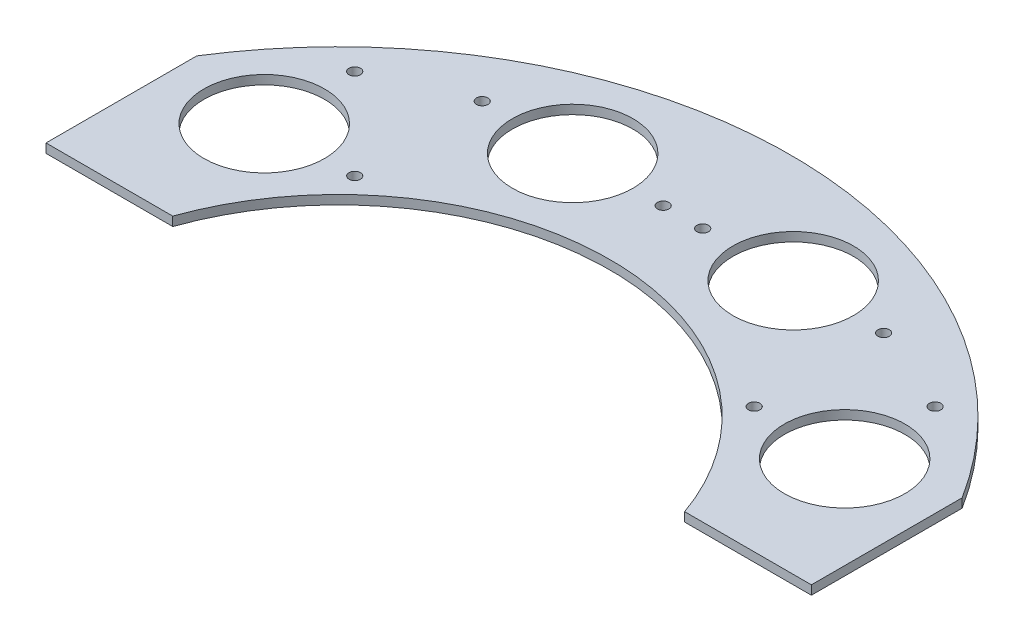
SolidWorks part; units mm, degrees
ref_plane "Front Plane" through (0, 0, 0) normal (0, 0, 1) x (1, 0, 0)
ref_plane "Top Plane" through (0, 0, 0) normal (0, 1, 0) x (1, 0, 0)
ref_plane "Right Plane" through (0, 0, 0) normal (1, 0, 0) x (0, 0, -1)
sketch "Sketch2" [suppressed] plane through (0, 0, 0) normal (0, 1, 0) x (1, 0, 0)
  line L0 (-25, 150) -> (25, 150)
  line L1 (-25, 0) -> (-25, 150) construction
  line L2 (0, 0) -> (-37.08, 101.61) construction
  line L3 (0, 0) -> (-82.9172, 69.4568) construction
  arc A0 (-25, 150) -> (0, -147.902) centre (-25, 0) ccw
  arc A1 (0, -147.902) -> (25, 150) centre (25, 0) ccw
  circle A2 centre (-37.08, 101.61) radius 20
  circle A3 centre (-82.9172, 69.4568) radius 20
  circle A4 centre (-106.5368, 18.6928) radius 20
  dimension "D1" = 300
  dimension "D2" = 300
  dimension "D5" = 40
  dimension "D3" = 50
  dimension "D4" = 25
  dimension "D6" = 12.08
  dimension "D7" = 48.39
  dimension "D9" = 30
sketch "Sketch3" plane through (0, 0, 0) normal (0, 1, 0) x (1, 0, 0)
  line L0 (-126.8858, -16.7898) -> (-84.8717, -16.7898)
  line L6 (-175, -125) -> (-139.6509, -99.7506) construction
  line L7 (-36.5556, 67.5067) -> (-27.2905, 38.9915) construction
  line L8 (-96.2239, 24.9107) -> (-71.9654, 7.2859) construction
  line L9 (-90.0178, -46.7898) -> (0, -46.7898) construction
  line L10 (0, -55) -> (0, 55) construction
  line L11 (-175, -16.7898) -> (-146.9694, -16.7898)
  line L12 (-126.8858, -16.7898) -> (-126.8858, 33.2102)
  line L13 (126.8858, -16.7898) -> (126.8858, 33.2102)
  line L14 (0, 0) -> (0, 43.228) construction
  line L17 (-19.0404, 13.6003) -> (-17.289, 8.2102) construction
  line L20 (84.8717, -16.7898) -> (126.8858, -16.7898)
  line L21 (-11.8672, -8.4766) -> (-9.166, -16.7898) construction
  circle A0 centre (-36.5556, 67.5067) radius 20
  circle A1 centre (-96.2239, 24.9107) radius 20
  circle A3 centre (36.5556, 67.5067) radius 20
  circle A4 centre (96.2239, 24.9107) radius 20
  arc A8 (84.8717, -16.7898) -> (-84.8717, -16.7898) centre (0, -46.7898) ccw
  arc A9 (126.8858, 33.2102) -> (-126.8858, 33.2102) centre (0, -46.7898) ccw
  point P0 (0, 0)
  point P2 (0, 0)
  point P10 (0, -46.7898)
  point P13 (0, 0)
  point P15 (0, 0)
  point P31 (0, 0)
  point P33 (0, 0)
  point P35 (0, 0)
  point P39 (0, 0)
  dimension "D3" = 40
  dimension "D7" = 40
  dimension "D4" = 90.0178
  dimension "D5" = 150
  dimension "D6" = 120
  dimension "D9" = 36
  dimension "D10" = 36
  dimension "D12" = 120
  dimension "D15" = 30
  dimension "D16" = 50
  dimension "D2" = 18
extrude "Boss-Extrude3" add sketch "Sketch3" along normal blind 3
hole_wizard "#10-24 Tapped Hole1" positions "Sketch4" profile "Sketch5" tap size "#10-24" standard "ANSI Inch" end condition through all
sketch "Sketch4" plane through (0, 3, 0) normal (0, 1, 0) x (1, 0, 0)
  point P0 (-66.2239, 24.9107)
  point P2 (-96.2239, 54.9107)
  point P4 (-66.5556, 67.5067)
  point P6 (-6.5556, 67.5067)
  point P8 (6.5556, 67.5067)
  point P10 (66.5556, 67.5067)
  point P12 (96.2239, 54.9107)
  point P14 (66.2239, 24.9107)
  point P17 (0, 0)
  point P19 (0, 0)
  point P20 (0, 0)
  point P23 (0, 0)
  point P24 (0, 0)
  point P26 (0, 0)
  point P28 (0, 0)
  dimension "D1" = 30
  dimension "D2" = 30
  dimension "D3" = 30
  dimension "D4" = 30
  dimension "D5" = 30
  dimension "D6" = 30
  dimension "D7" = 30
  dimension "D8" = 30
sketch "Sketch5" plane through (-66.2239, 3, -24.9107) normal (1, 0, 0) x (0, 0, 1)
  line L0 (0, 0) -> (0, 3)
  line L1 (0, 3) -> (1.8986, 3)
  line L2 (1.8986, 3) -> (1.8986, 0)
  line L5 (1.8986, 0) -> (0, 0)
  line L11 (0, -6.35) -> (0, 107.95) construction
  dimension "Thru Tap Drill Dia." = 3.7973
  dimension "Thru Tap Drill Depth" = 3
cosmetic thread "Hole Thread1" parameters "D2"=4.826
cosmetic thread "Hole Thread2" parameters "D2"=4.826
cosmetic thread "Hole Thread3" parameters "D2"=4.826
cosmetic thread "Hole Thread4" parameters "D2"=4.826
cosmetic thread "Hole Thread5" parameters "D2"=4.826
cosmetic thread "Hole Thread6" parameters "D2"=4.826
cosmetic thread "Hole Thread7" parameters "D2"=4.826
cosmetic thread "Hole Thread8" parameters "D2"=4.826
equation "\"D2@Sketch2\"=\"D1@Sketch2\""
equation "\"D7@Sketch3\"=\"D3@Sketch3\""
equation "\"D2@Sketch4\"=\"D1@Sketch4\""
equation "\"D3@Sketch4\"=\"D1@Sketch4\""
equation "\"D4@Sketch4\"=\"D1@Sketch4\""
equation "\"D5@Sketch4\"=\"D1@Sketch4\""
equation "\"D6@Sketch4\"=\"D1@Sketch4\""
equation "\"D7@Sketch4\"=\"D1@Sketch4\""
equation "\"D8@Sketch4\"=\"D1@Sketch4\""
